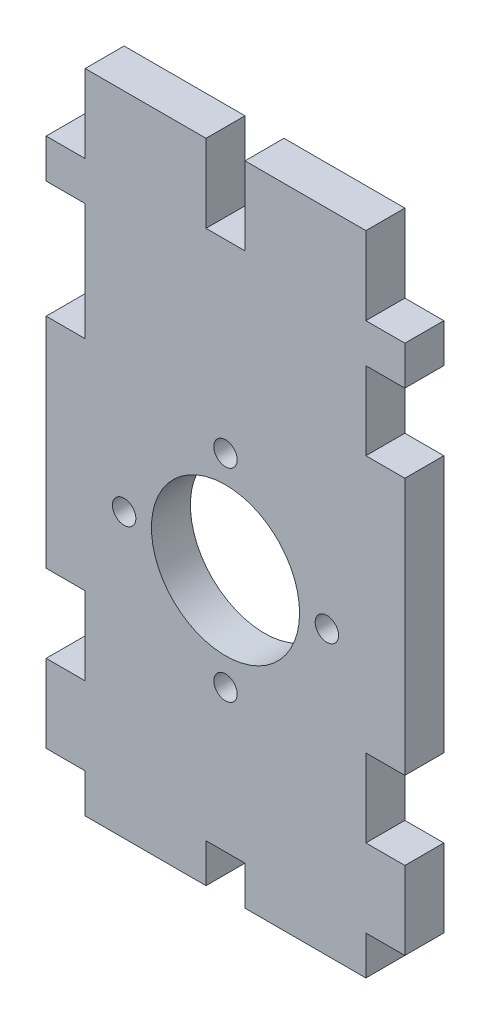
SolidWorks part; units mm, degrees
ref_plane "Plan de face" through (0, 0, 0) normal (0, 0, 1) x (1, 0, 0)
ref_plane "Plan de dessus" through (0, 0, 0) normal (0, 1, 0) x (1, 0, 0)
ref_plane "Plan de droite" through (0, 0, 0) normal (1, 0, 0) x (0, 0, -1)
sketch "Esquisse1" plane through (0, 0, 0) normal (0, 0, 1) x (1, 0, 0)
  line L1 (0, 0) -> (46, 0)
  line L2 (0, 0) -> (0, 73)
  line L3 (0, 73) -> (46, 73)
  line L4 (46, 0) -> (46, 73)
  circle A0 centre (23, 31.275) radius 9.5
  dimension "D2" = 19
  dimension "D1" = 31.275
  dimension "D3" = 46
  dimension "D4" = 23
  dimension "D5" = 73
extrude "Boss.-Extru.1" add sketch "Esquisse1" along normal blind 5
sketch "Esquisse2" plane through (0, 0, 5) normal (0, 0, 1) x (1, 0, 0)
  line L0 (46, 0) -> (46, 73) construction
  line L1 (46, 63) -> (41, 63)
  line L2 (46, 63) -> (46, 53)
  line L3 (46, 53) -> (41, 53)
  line L4 (41, 63) -> (41, 53)
  line L5 (5, 73) -> (5, 68)
  line L6 (46, 73) -> (0, 73) construction
  line L7 (46, 20) -> (41, 20)
  line L8 (46, 20) -> (46, 10)
  line L9 (46, 10) -> (41, 10)
  line L10 (41, 20) -> (41, 10)
  line L11 (0, 0) -> (46, 0) construction
  line L12 (23, 31.275) -> (23, 0) construction
  line L13 (5, 20) -> (5, 10)
  line L14 (0, 10) -> (5, 10)
  line L15 (0, 20) -> (0, 10)
  line L16 (0, 20) -> (5, 20)
  line L17 (5, 63) -> (5, 48)
  line L18 (0, 48) -> (5, 48)
  line L19 (0, 63) -> (0, 48)
  line L20 (0, 63) -> (5, 63)
  line L21 (46, 73) -> (41, 73)
  line L22 (46, 73) -> (46, 68)
  line L23 (46, 68) -> (41, 68)
  line L24 (41, 73) -> (41, 68)
  line L25 (0, 68) -> (5, 68)
  line L26 (0, 73) -> (0, 68)
  line L27 (0, 73) -> (5, 73)
  line L28 (20.5, 73) -> (20.5, 68)
  line L29 (46, 73) -> (0, 73) construction
  line L30 (30.5, 68) -> (15.5, 68) construction
  line L31 (25.5, 73) -> (25.5, 68)
  line L32 (20.5, 73) -> (25.5, 73)
  line L33 (25.5, 68) -> (20.5, 68)
  circle A0 centre (23, 44.275) radius 1.5
  circle A3 centre (36, 31.275) radius 1.5
  circle A4 centre (23, 18.275) radius 1.5
  circle A5 centre (10, 31.275) radius 1.5
  point P2 (23, 31.275)
  point P14 (23, 31.275)
  dimension "D1" = 3
  dimension "D3" = 10
  dimension "D4" = 10
  dimension "D5" = 10
  dimension "D6" = 10
  dimension "D7" = 15
  dimension "D8" = 5
  dimension "D9" = 5
  dimension "D10" = 5
  dimension "D11" = 5
  dimension "D2" = 4
extrude "Enlèv. mat.-Extru.1" cut sketch "Esquisse2" against normal blind 5
sketch "Esquisse3" plane through (0, 0, 0) normal (0, 0, -1) x (-1, 0, 0)
  line L0 (-23, 31.275) -> (-23, 68) construction
  line L1 (-41, 73) -> (-25.5, 73)
  line L2 (-41, 73) -> (-41, 78)
  line L3 (-41, 78) -> (-25.5, 78)
  line L4 (-25.5, 73) -> (-25.5, 78)
  line L5 (-20.5, 68) -> (-25.5, 68) construction
  line L6 (-20.5, 73) -> (-20.5, 78)
  line L7 (-5, 78) -> (-20.5, 78)
  line L8 (-5, 73) -> (-5, 78)
  line L9 (-5, 73) -> (-20.5, 73)
  line L10 (-25.5, 68) -> (-25.5, 73) construction
  line L12 (0, 0) -> (-46, 0) construction
  line L13 (-41, 0) -> (-25.5, 0)
  line L14 (-41, 0) -> (-41, -5)
  line L15 (-41, -5) -> (-25.5, -5)
  line L16 (-25.5, 0) -> (-25.5, -5)
  line L17 (-5, 0) -> (-5, -5)
  line L18 (-20.5, 0) -> (-20.5, -5)
  line L19 (-5, -5) -> (-20.5, -5)
  line L20 (-5, 0) -> (-20.5, 0)
  dimension "D1" = 5
  dimension "D2" = 5
  dimension "D3" = 5
  dimension "D4" = 15.5
extrude "Boss.-Extru.2" add sketch "Esquisse3" against normal blind 5
